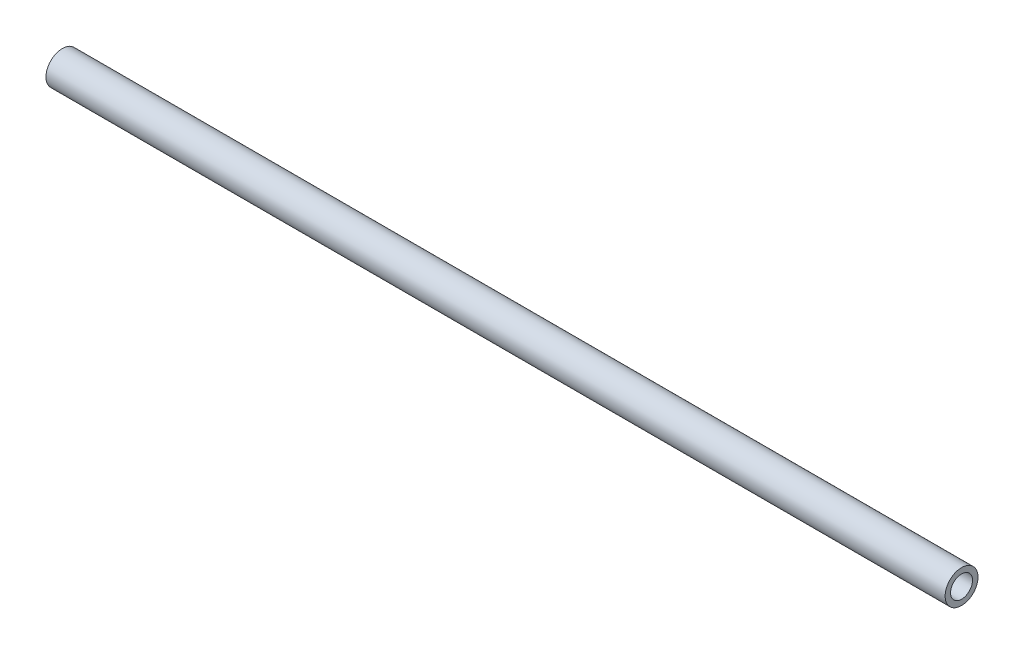
SolidWorks part; units mm, degrees
material "3.3535 (EN-AW 5754)"
ref_plane "Front" through (0, 0, 0) normal (0, 0, 1) x (1, 0, 0)
ref_plane "Top" through (0, 0, 0) normal (0, 1, 0) x (1, 0, 0)
ref_plane "Right" through (0, 0, 0) normal (1, 0, 0) x (0, 0, -1)
sketch "Esquisse1" plane through (0, 0, 0) normal (1, 0, 0) x (0, 0, -1)
  circle A0 centre (0, 0) radius 3
  dimension "D1" = 6
extrude "Extru.-Mince1" add sketch "Esquisse1" along normal mid plane 164 thin thin type one direction reverse wall 1
